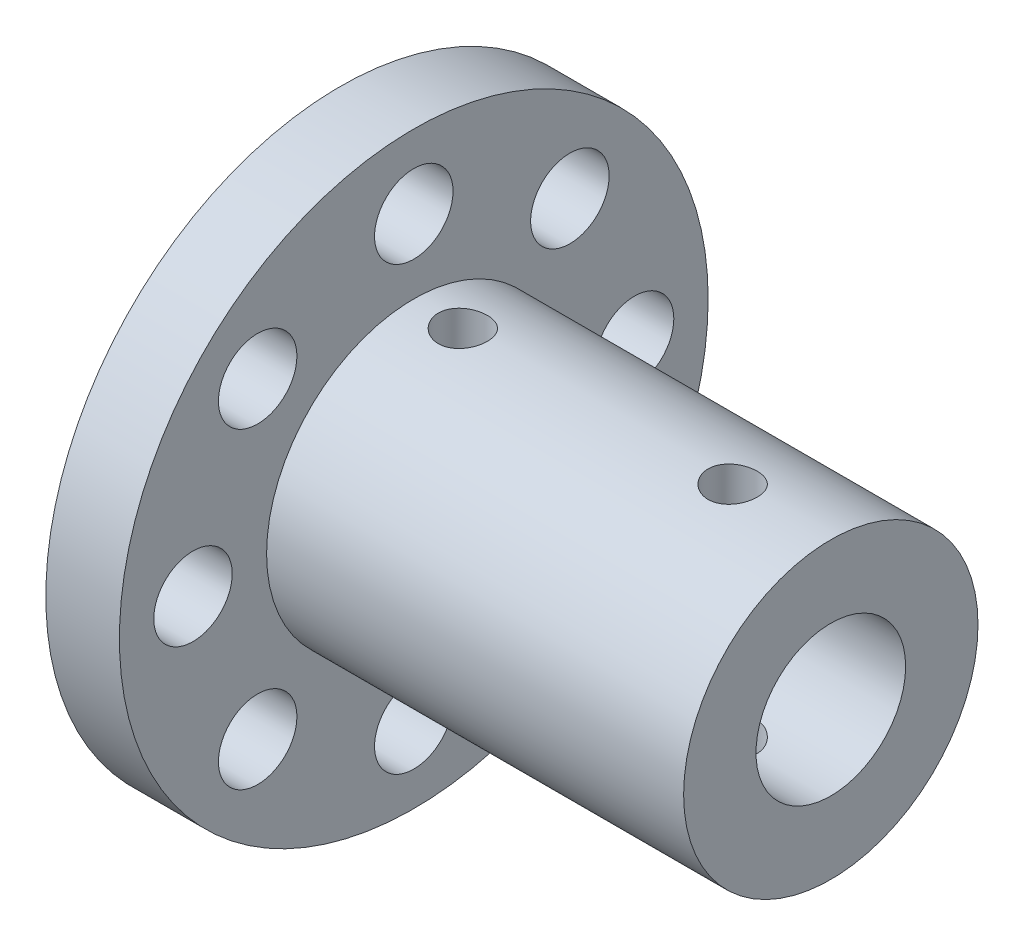
SolidWorks part; units mm, degrees
other "Preload Coupling and Lock Disc"
ref_plane "Front Plane" through (0, 0, 0) normal (0, 0, 1) x (1, 0, 0)
ref_plane "Top Plane" through (0, 0, 0) normal (0, 1, 0) x (1, 0, 0)
ref_plane "Right Plane" through (0, 0, 0) normal (1, 0, 0) x (0, 0, -1)
sketch3d "Coupling barrel sketch datum points"
  point P0 (-7, -29, -19.5)
  point P1 (-7, -19, -19.5)
  point P2 (-7, -29, -9.5)
ref_plane "Coupling barrel sketch plane" through (-7, 0, 0) normal (1, 0, 0) x (0, 0, -1)
sketch "Coupling barrel sketch" plane through (-7, 0, 0) normal (1, 0, 0) x (0, 0, -1)
  circle A0 centre (19.5, -29) radius 6
extrude "Coupling barrel" add sketch "Coupling barrel sketch" along normal blind 20 separate body
sketch3d "Service lock disc sketch datum points"
  point P0 (-7, -29, -19.5)
  point P1 (-7, -19, -19.5)
  point P2 (-7, -29, -9.5)
ref_plane "Service lock disc sketch plane" through (-7, 0, 0) normal (1, 0, 0) x (0, 0, -1)
sketch "Service lock disc sketch" plane through (-7, 0, 0) normal (1, 0, 0) x (0, 0, -1)
  circle A0 centre (19.5, -29) radius 12
extrude "Service lock disc" add sketch "Service lock disc sketch" along normal blind 3
sketch3d "Shaft running bore sketch datum points"
  point P0 (-7.1, -29, -19.5)
  point P1 (-7.1, -19, -19.5)
  point P2 (-7.1, -29, -9.5)
ref_plane "Shaft running bore sketch plane" through (-7.1, 0, 0) normal (1, 0, 0) x (0, 0, -1)
sketch "Shaft running bore sketch" plane through (-7.1, 0, 0) normal (1, 0, 0) x (0, 0, -1)
  circle A0 centre (19.5, -29) radius 3.05
extrude "Shaft running bore" cut sketch "Shaft running bore sketch" along normal blind 20.2
sketch3d "Torque cross pin hole 1 sketch datum points"
  point P0 (-2, -42, -19.5)
  point P1 (8, -42, -19.5)
  point P2 (-2, -42, -29.5)
ref_plane "Torque cross pin hole 1 sketch plane" through (0, -42, 0) normal (0, 1, 0) x (1, 0, 0)
sketch "Torque cross pin hole 1 sketch" plane through (0, -42, 0) normal (0, 1, 0) x (1, 0, 0)
  circle A0 centre (-2, 19.5) radius 1
extrude "Torque cross pin hole 1" cut sketch "Torque cross pin hole 1 sketch" along normal blind 26
sketch3d "Torque cross pin hole 2 sketch datum points"
  point P0 (9, -42, -19.5)
  point P1 (19, -42, -19.5)
  point P2 (9, -42, -29.5)
ref_plane "Torque cross pin hole 2 sketch plane" through (0, -42, 0) normal (0, 1, 0) x (1, 0, 0)
sketch "Torque cross pin hole 2 sketch" plane through (0, -42, 0) normal (0, 1, 0) x (1, 0, 0)
  circle A0 centre (9, 19.5) radius 1
extrude "Torque cross pin hole 2" cut sketch "Torque cross pin hole 2 sketch" along normal blind 26
sketch3d "Service lock position 1 sketch datum points"
  point P0 (-7.1, -20, -19.5)
  point P1 (-7.1, -10, -19.5)
  point P2 (-7.1, -20, -9.5)
ref_plane "Service lock position 1 sketch plane" through (-7.1, 0, 0) normal (1, 0, 0) x (0, 0, -1)
sketch "Service lock position 1 sketch" plane through (-7.1, 0, 0) normal (1, 0, 0) x (0, 0, -1)
  circle A0 centre (19.5, -20) radius 1.6
extrude "Service lock position 1" cut sketch "Service lock position 1 sketch" along normal blind 3.2
sketch3d "Service lock position 2 sketch datum points"
  point P0 (-7.1, -22.636, -13.136)
  point P1 (-7.1, -12.636, -13.136)
  point P2 (-7.1, -22.636, -3.136)
ref_plane "Service lock position 2 sketch plane" through (-7.1, 0, 0) normal (1, 0, 0) x (0, 0, -1)
sketch "Service lock position 2 sketch" plane through (-7.1, 0, 0) normal (1, 0, 0) x (0, 0, -1)
  circle A0 centre (13.136, -22.636) radius 1.6
extrude "Service lock position 2" cut sketch "Service lock position 2 sketch" along normal blind 3.2
sketch3d "Service lock position 3 sketch datum points"
  point P0 (-7.1, -29, -10.5)
  point P1 (-7.1, -19, -10.5)
  point P2 (-7.1, -29, -0.5)
ref_plane "Service lock position 3 sketch plane" through (-7.1, 0, 0) normal (1, 0, 0) x (0, 0, -1)
sketch "Service lock position 3 sketch" plane through (-7.1, 0, 0) normal (1, 0, 0) x (0, 0, -1)
  circle A0 centre (10.5, -29) radius 1.6
extrude "Service lock position 3" cut sketch "Service lock position 3 sketch" along normal blind 3.2
sketch3d "Service lock position 4 sketch datum points"
  point P0 (-7.1, -35.364, -13.136)
  point P1 (-7.1, -25.364, -13.136)
  point P2 (-7.1, -35.364, -3.136)
ref_plane "Service lock position 4 sketch plane" through (-7.1, 0, 0) normal (1, 0, 0) x (0, 0, -1)
sketch "Service lock position 4 sketch" plane through (-7.1, 0, 0) normal (1, 0, 0) x (0, 0, -1)
  circle A0 centre (13.136, -35.364) radius 1.6
extrude "Service lock position 4" cut sketch "Service lock position 4 sketch" along normal blind 3.2
sketch3d "Service lock position 5 sketch datum points"
  point P0 (-7.1, -38, -19.5)
  point P1 (-7.1, -28, -19.5)
  point P2 (-7.1, -38, -9.5)
ref_plane "Service lock position 5 sketch plane" through (-7.1, 0, 0) normal (1, 0, 0) x (0, 0, -1)
sketch "Service lock position 5 sketch" plane through (-7.1, 0, 0) normal (1, 0, 0) x (0, 0, -1)
  circle A0 centre (19.5, -38) radius 1.6
extrude "Service lock position 5" cut sketch "Service lock position 5 sketch" along normal blind 3.2
sketch3d "Service lock position 6 sketch datum points"
  point P0 (-7.1, -35.364, -25.864)
  point P1 (-7.1, -25.364, -25.864)
  point P2 (-7.1, -35.364, -15.864)
ref_plane "Service lock position 6 sketch plane" through (-7.1, 0, 0) normal (1, 0, 0) x (0, 0, -1)
sketch "Service lock position 6 sketch" plane through (-7.1, 0, 0) normal (1, 0, 0) x (0, 0, -1)
  circle A0 centre (25.864, -35.364) radius 1.6
extrude "Service lock position 6" cut sketch "Service lock position 6 sketch" along normal blind 3.2
sketch3d "Service lock position 7 sketch datum points"
  point P0 (-7.1, -29, -28.5)
  point P1 (-7.1, -19, -28.5)
  point P2 (-7.1, -29, -18.5)
ref_plane "Service lock position 7 sketch plane" through (-7.1, 0, 0) normal (1, 0, 0) x (0, 0, -1)
sketch "Service lock position 7 sketch" plane through (-7.1, 0, 0) normal (1, 0, 0) x (0, 0, -1)
  circle A0 centre (28.5, -29) radius 1.6
extrude "Service lock position 7" cut sketch "Service lock position 7 sketch" along normal blind 3.2
sketch3d "Service lock position 8 sketch datum points"
  point P0 (-7.1, -22.636, -25.864)
  point P1 (-7.1, -12.636, -25.864)
  point P2 (-7.1, -22.636, -15.864)
ref_plane "Service lock position 8 sketch plane" through (-7.1, 0, 0) normal (1, 0, 0) x (0, 0, -1)
sketch "Service lock position 8 sketch" plane through (-7.1, 0, 0) normal (1, 0, 0) x (0, 0, -1)
  circle A0 centre (25.864, -22.636) radius 1.6
extrude "Service lock position 8" cut sketch "Service lock position 8 sketch" along normal blind 3.2
